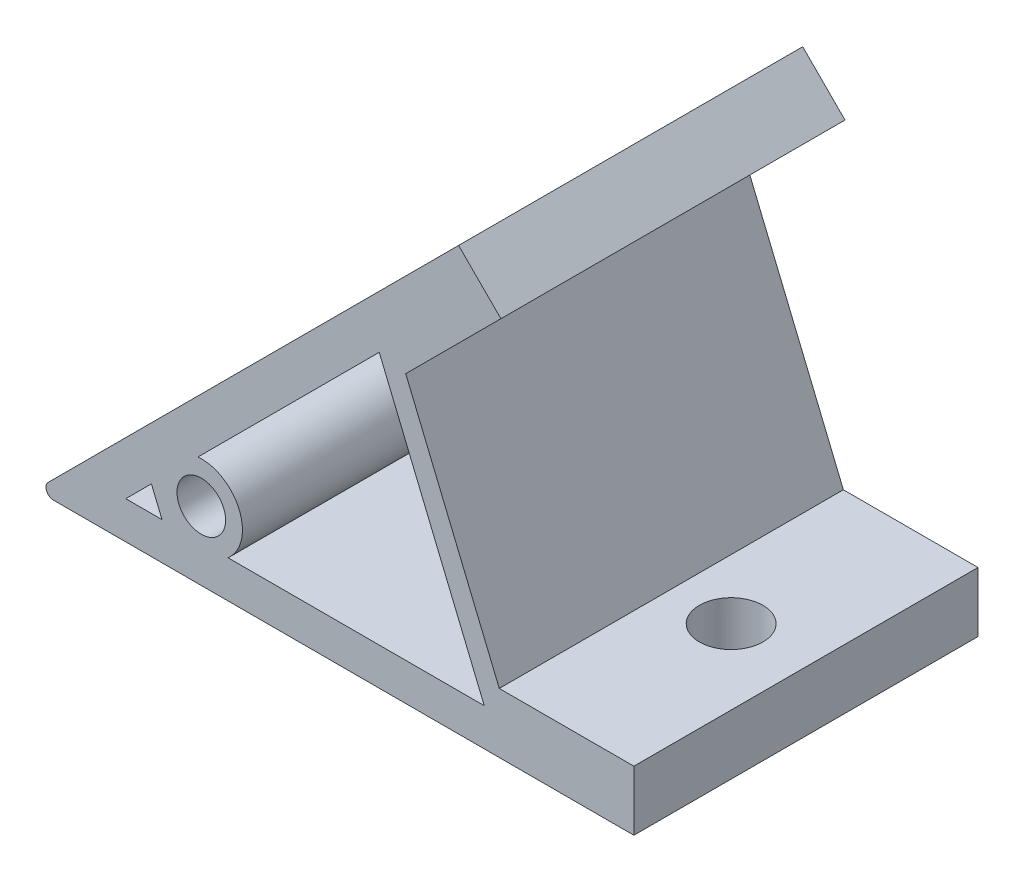
SolidWorks part; units mm, degrees
ref_plane "前视基准面" through (0, 0, 0) normal (0, 0, 1) x (1, 0, 0)
ref_plane "上视基准面" through (0, 0, 0) normal (0, 1, 0) x (1, 0, 0)
ref_plane "右视基准面" through (0, 0, 0) normal (1, 0, 0) x (0, 0, -1)
sketch "草图1" plane through (0, 0, 0) normal (0, 0, 1) x (1, 0, 0)
  line B0 (-77.5858, 0) -> (0, 0)
  line B1 (-67.9289, 5) -> (-63.0745, 5)
  line B2 (-54.2575, 5) -> (-20, 5)
  line B3 (-17.9955, 8) -> (0, 8)
  line B4 (-78.2929, 1.7071) -> (-23.4315, 56.5685)
  line B5 (-67.9289, 5) -> (-64.4963, 8.4326)
  line B6 (-58.2617, 14.6672) -> (-34.0381, 38.8909)
  line B7 (-30.4993, 38.187) -> (-17.7746, 50.9117)
  line B8 (0, 0) -> (0, 8)
  line B9 (-17.7746, 50.9117) -> (-23.4315, 56.5685)
  line B10 (-20, 5) -> (-34.0381, 38.8909)
  line B11 (-17.9955, 8) -> (-30.4993, 38.187)
  line B12 (-63.0745, 5) -> (-64.4963, 8.4326)
  arc B13 (-78.2929, 1.7071) -> (-77.5858, 0) centre (-77.5858, 1) ccw
  circle B14 centre (-57.8269, 9.1844) radius 3.25
  arc B15 (-54.2575, 5) -> (-58.2617, 14.6672) centre (-57.8269, 9.1844) ccw
sketch_block_instance "A$C18907C9D-1"
sketch_block "A$C18907C9D"
extrude "凸台-拉伸1" add sketch "草图1" along normal mid plane 46
sketch "草图3" plane through (0, 8, 0) normal (0, 1, 0) x (1, 0, 0)
  line L0 (0, -23) -> (0, 23) construction
  circle A0 centre (-10, 0) radius 4.25
  dimension "D1" = 10
extrude "切除-拉伸1" cut sketch "草图3" against normal blind 17
sketch "草图4" plane through (-12.5317, -5.1908, 0) normal (0.9239, 0.3827, 0) x (0, 0, -1)
  line L0 (-23, 30.6147) -> (23, 30.6147) construction
  line L1 (-23, 14.2776) -> (-23, 46.9517) construction
  line L2 (23, 14.2776) -> (23, 46.9517) construction
ref_plane "基准面2" through (-11.7157, 28.2843, 0) normal (-0.3827, 0.9239, 0) x (0.9239, 0.3827, 0)
mirror "镜向1" about plane through (-11.7157, 28.2843, 0) normal (-0.3827, 0.9239, 0) of "切除-拉伸1"
